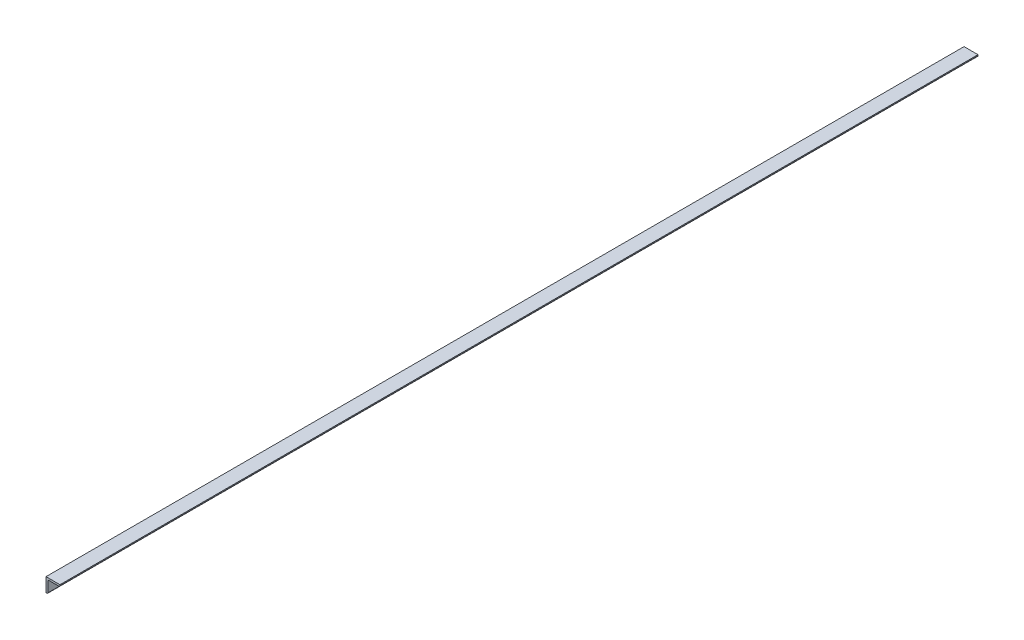
SolidWorks part; units mm, degrees
material "ASTM A36 Steel"
ref_plane "Front Plane" through (0, 0, 0) normal (0, 0, 1) x (1, 0, 0)
ref_plane "Top Plane" through (0, 0, 0) normal (0, 1, 0) x (1, 0, 0)
ref_plane "Right Plane" through (0, 0, 0) normal (1, 0, 0) x (0, 0, -1)
sketch "Sketch1" plane through (0, 0, 0) normal (0, 0, 1) x (1, 0, 0)
  line L0 (-8.625, 38.8125) -> (-38.625, 38.8125)
  line L1 (-38.625, 38.8125) -> (-38.625, 8.8125)
  line L2 (-38.625, 8.8125) -> (-36.625, 8.8125)
  line L3 (-34.625, 10.8125) -> (-34.625, 32.8125)
  line L4 (-32.625, 34.8125) -> (-10.625, 34.8125)
  line L5 (-8.625, 36.8125) -> (-8.625, 38.8125)
  arc A0 (-36.625, 8.8125) -> (-34.625, 10.8125) centre (-36.625, 10.8125) ccw
  arc A1 (-10.625, 34.8125) -> (-8.625, 36.8125) centre (-10.625, 36.8125) ccw
  arc A2 (-34.625, 32.8125) -> (-32.625, 34.8125) centre (-32.625, 32.8125) cw
  point P8 (-34.625, 8.8125)
  point P11 (-8.625, 34.8125)
  dimension "D5" = 2
  dimension "D1" = 30
  dimension "D2" = 30
  dimension "D3" = 4
  dimension "D4" = 4
extrude "Boss-Extrude1" add sketch "Sketch1" along normal blind 1975
